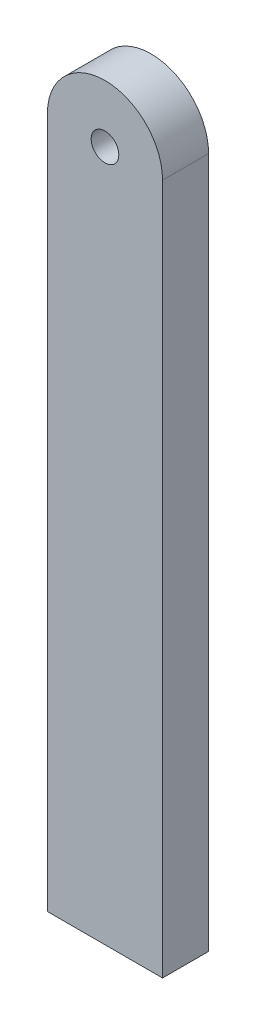
SolidWorks part; units mm, degrees
ref_plane "Front Plane" through (0, 0, 0) normal (0, 0, 1) x (1, 0, 0)
ref_plane "Top Plane" through (0, 0, 0) normal (0, 1, 0) x (1, 0, 0)
ref_plane "Right Plane" through (0, 0, 0) normal (1, 0, 0) x (0, 0, -1)
sketch "Sketch1" plane through (0, 0, 0) normal (0, 0, 1) x (1, 0, 0)
  line L1 (-12.5, -75) -> (12.5, -75)
  line L2 (-12.5, -75) -> (-12.5, 75)
  line L4 (12.5, -75) -> (12.5, 75)
  line L5 (-12.5, -75) -> (12.5, 75) construction
  line L6 (-12.5, 75) -> (12.5, -75) construction
  arc A0 (-12.5, 75) -> (12.5, 75) centre (0, 75) cw
  circle A1 centre (0, 75) radius 3
  point P0 (0, 0)
  dimension "D3" = 6
  dimension "D1" = 25
  dimension "D2" = 150
extrude "Boss-Extrude1" add sketch "Sketch1" along normal blind 10
